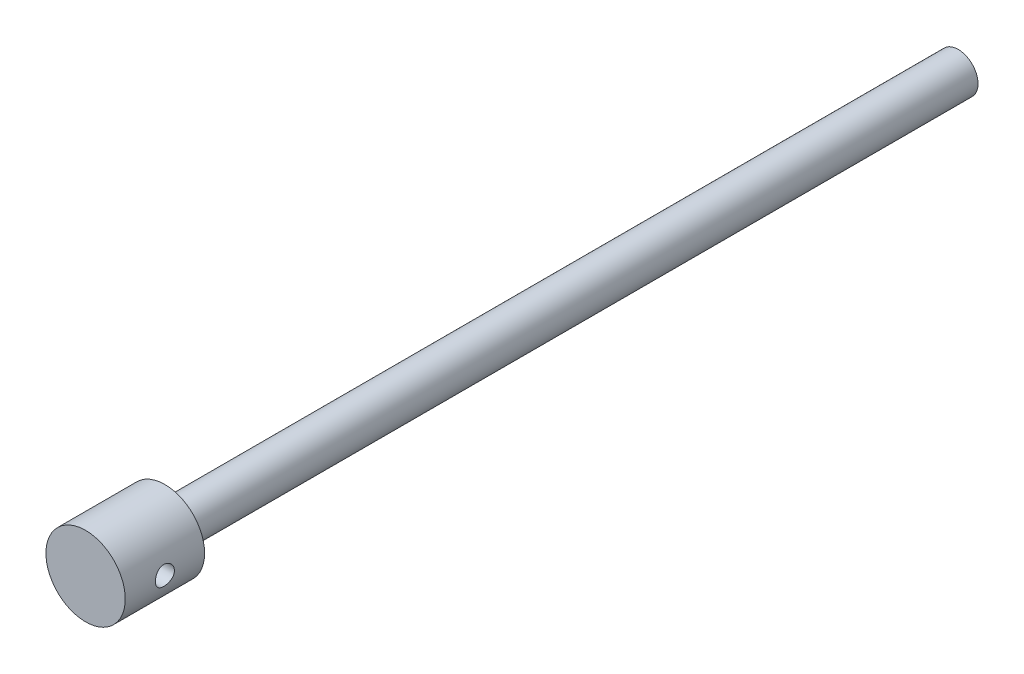
SolidWorks part; units mm, degrees
ref_plane "Front Plane" through (0, 0, 0) normal (0, 0, 1) x (1, 0, 0)
ref_plane "Top Plane" through (0, 0, 0) normal (0, 1, 0) x (1, 0, 0)
ref_plane "Right Plane" through (0, 0, 0) normal (1, 0, 0) x (0, 0, -1)
sketch "Sketch1" plane through (0, 0, 0) normal (0, 0, 1) x (1, 0, 0)
  circle A0 centre (0, 0) radius 25
  dimension "D1" = 50
extrude "Boss-Extrude1" add sketch "Sketch1" along normal mid plane 50
sketch "Sketch2" plane through (0, 0, 0) normal (1, 0, 0) x (0, 0, -1)
  circle A0 centre (0, 0) radius 6
  dimension "D1" = 12
extrude "Cut-Extrude1" cut sketch "Sketch2" against normal mid plane 70
sketch "Sketch3" plane through (0, 0, -25) normal (0, 0, -1) x (-1, 0, 0)
  circle A0 centre (0, 0) radius 12.5
  dimension "D1" = 25
extrude "Boss-Extrude2" add sketch "Sketch3" along normal blind 500
cosmetic thread "Cosmetic Thread1" parameters "D2"=20.704
cosmetic thread "Cosmetic Thread2" parameters "D2"=20.704
